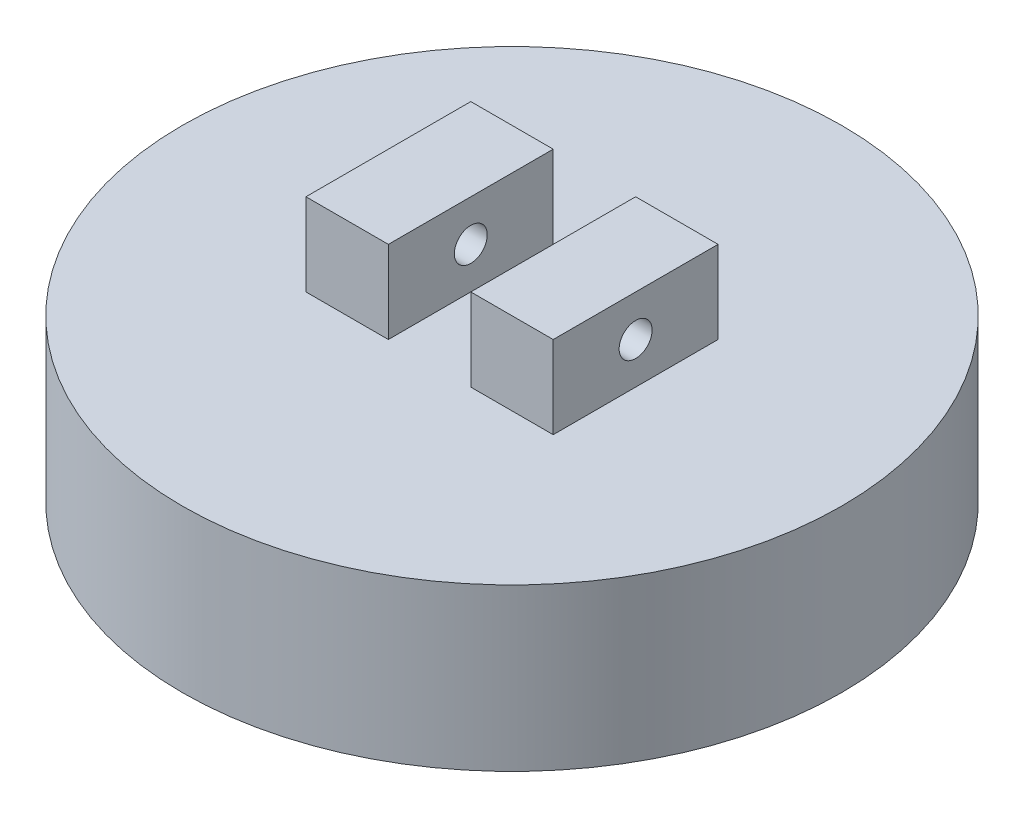
SolidWorks part; units mm, degrees
ref_plane "Alzado" through (0, 0, 0) normal (0, 0, 1) x (1, 0, 0)
ref_plane "Planta" through (0, 0, 0) normal (0, 1, 0) x (1, 0, 0)
ref_plane "Vista lateral" through (0, 0, 0) normal (1, 0, 0) x (0, 0, -1)
sketch "Croquis2" plane through (0, 0, 0) normal (0, 1, 0) x (1, 0, 0)
  circle A0 centre (0, 0) radius 20
  dimension "D1" = 40
extrude "Saliente-Extruir1" add sketch "Croquis2" along normal blind 9.8
sketch "Croquis3" plane through (0, 9.8, 0) normal (0, 1, 0) x (1, 0, 0)
  line L0 (-2.5, 0) -> (2.5, 0) construction
  line L1 (2.5, -5) -> (2.5, 5)
  line L2 (-2.5, -5) -> (-2.5, 5)
  line L3 (-2.5, 5) -> (-7.5, 5)
  line L4 (-7.5, 5) -> (-7.5, -5)
  line L5 (-7.5, -5) -> (-2.5, -5)
  line L6 (2.5, 5) -> (7.5, 5)
  line L7 (7.5, 5) -> (7.5, -5)
  line L8 (7.5, -5) -> (2.5, -5)
  point P5 (0, 0)
  point P7 (0, 0)
  point P11 (2.5, 0)
  point P14 (-2.5, 0)
  dimension "D1" = 5
  dimension "D2" = 10
  dimension "D3" = 10
  dimension "D4" = 5
  dimension "D5" = 5
extrude "Saliente-Extruir2" add sketch "Croquis3" along normal blind 5
sketch "Croquis4" plane through (-7.5, 0, 0) normal (-1, 0, 0) x (0, 0, 1)
  line L0 (0, 9.8) -> (0, 14.8) construction
  line L1 (20, 9.8) -> (-20, 9.8) construction
  line L2 (-5, 14.8) -> (5, 14.8) construction
  circle A0 centre (0, 12.3) radius 1
  dimension "D1" = 2
  dimension "D2" = 2.5
extrude "Cortar-Extruir1" cut sketch "Croquis4" against normal through all
